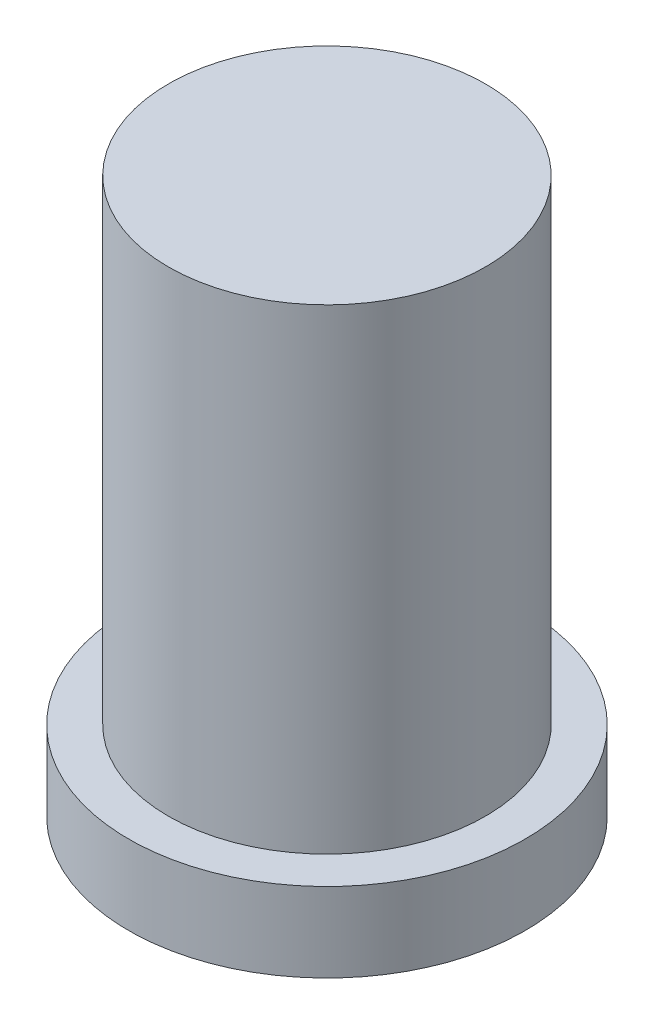
SolidWorks part; units mm, degrees
ref_plane "Front Plane" through (0, 0, 0) normal (0, 0, 1) x (1, 0, 0)
ref_plane "Top Plane" through (0, 0, 0) normal (0, 1, 0) x (1, 0, 0)
ref_plane "Right Plane" through (0, 0, 0) normal (1, 0, 0) x (0, 0, -1)
sketch "Sketch1" plane through (0, 0, 0) normal (0, 1, 0) x (1, 0, 0)
  circle A0 centre (0, 0) radius 4
  dimension "D1" = 8
extrude "Boss-Extrude1" add sketch "Sketch1" along normal blind 12
sketch "Sketch2" plane through (0, 0, 0) normal (0, -1, 0) x (-1, 0, 0)
  circle A0 centre (0, 0) radius 5
  dimension "D1" = 10
extrude "Boss-Extrude2" add sketch "Sketch2" along normal blind 2
